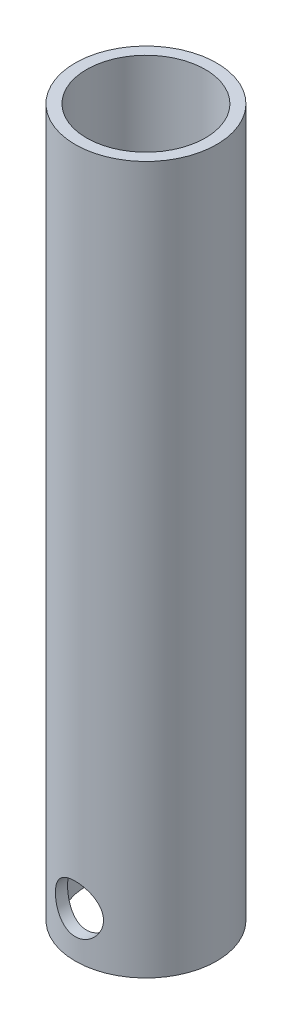
SolidWorks part; units mm, degrees
material "1060 Сплав"
ref_plane "Спереди" through (0, 0, 0) normal (0, 0, 1) x (1, 0, 0)
ref_plane "Сверху" through (0, 0, 0) normal (0, 1, 0) x (1, 0, 0)
ref_plane "Справа" through (0, 0, 0) normal (1, 0, 0) x (0, 0, -1)
sketch "Эскиз1" plane through (0, 0, 0) normal (0, 1, 0) x (1, 0, 0)
  circle A0 centre (0, 0) radius 12.5
  circle A1 centre (0, 0) radius 10.5
  dimension "D1" = 21
  dimension "D2" = 25
extrude "Бобышка-Вытянуть1" add sketch "Эскиз1" along normal blind 125
sketch "Эскиз2" plane through (0, 0, 0) normal (0, 0, 1) x (1, 0, 0)
  circle A0 centre (0, 8) radius 4.25
  dimension "D1" = 8.5
  dimension "D2" = 8
extrude "Вырез-Вытянуть1" cut sketch "Эскиз2" against normal through all and the other way through all
sketch "Эскиз4" plane through (0, 0, 0) normal (1, 0, 0) x (0, 0, -1)
  circle A0 centre (0, 56) radius 0.5
  dimension "D1" = 1
  dimension "D2" = 56
extrude "Вырез-Вытянуть3" cut sketch "Эскиз4" against normal blind 25
